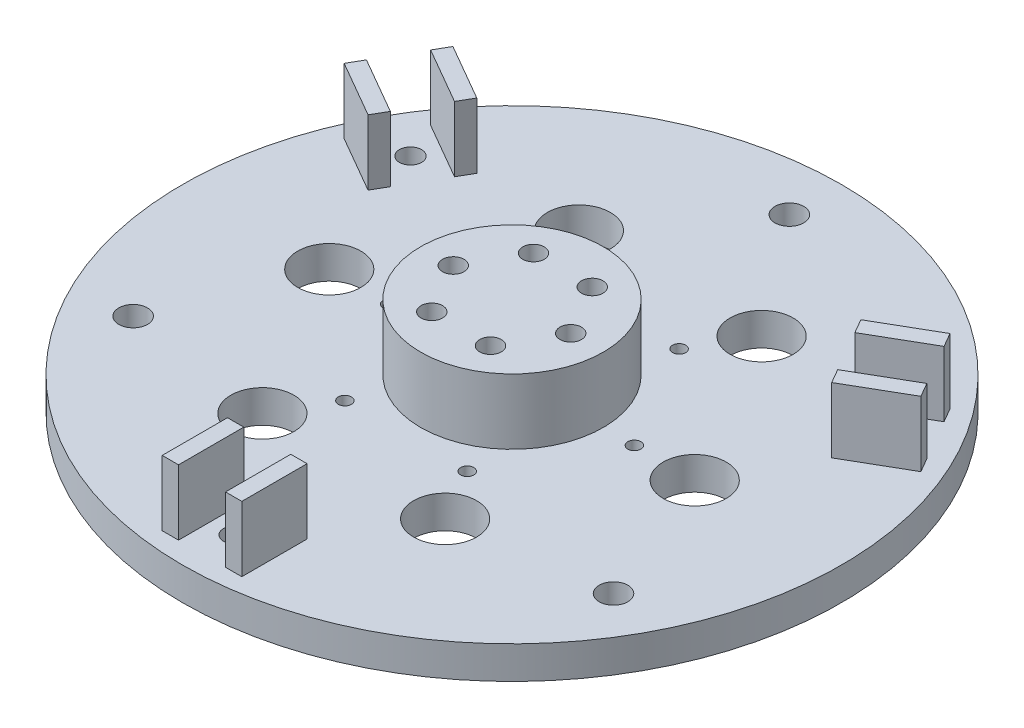
SolidWorks part; units mm, degrees
ref_plane "Front Plane" through (0, 0, 0) normal (0, 0, 1) x (1, 0, 0)
ref_plane "Top Plane" through (0, 0, 0) normal (0, 1, 0) x (1, 0, 0)
ref_plane "Right Plane" through (0, 0, 0) normal (1, 0, 0) x (0, 0, -1)
sketch "Sketch1" plane through (0, 0, 0) normal (0, 1, 0) x (1, 0, 0)
  circle A0 centre (0, 0) radius 50.5
  dimension "D1" = 101
extrude "Boss-Extrude1" add sketch "Sketch1" along normal blind 5
sketch "Sketch3" plane through (0, 5, 0) normal (0, 1, 0) x (1, 0, 0)
  circle A0 centre (9, 0) radius 1.65
  circle A2 centre (4.5, -7.7942) radius 1.65
  circle A3 centre (-4.5, -7.7942) radius 1.65
  circle A4 centre (-9, 0) radius 1.65
  circle A5 centre (-4.5, 7.7942) radius 1.65
  circle A6 centre (4.5, 7.7942) radius 1.65
  circle A7 centre (0, 0) radius 14
  point P13 (0, 0)
  dimension "D2" = 3.3
  dimension "D3" = 6
  dimension "D4" = 28
  dimension "D1" = 9
extrude "Boss-Extrude2" add sketch "Sketch3" along normal blind 10
sketch "Sketch6" plane through (0, 5, 0) normal (0, 1, 0) x (1, 0, 0)
  line L1 (0, 0) -> (69.3461, 0) construction
  circle A0 centre (0, 0) radius 18.75 construction
  circle A3 centre (18.75, 0) radius 1
  circle A5 centre (9.375, -16.238) radius 1
  circle A6 centre (-9.375, -16.238) radius 1
  circle A7 centre (-18.75, 0) radius 1
  circle A8 centre (-9.375, 16.238) radius 1
  circle A9 centre (9.375, 16.238) radius 1
  point P18 (0, 0)
  point P22 (0, 0)
  dimension "D1" = 37.5
  dimension "D2" = 2
  dimension "D3" = 6
extrude "Cut-Extrude4" cut sketch "Sketch6" against normal blind 10
sketch "Sketch5" plane through (0, 5, 0) normal (0, 1, 0) x (1, 0, 0)
  circle A0 centre (0, 0) radius 28 construction
  circle A1 centre (28, 0) radius 4.835
  circle A5 centre (14, -24.2487) radius 4.835
  circle A6 centre (-14, -24.2487) radius 4.835
  circle A7 centre (-28, 0) radius 4.835
  circle A8 centre (-14, 24.2487) radius 4.835
  circle A9 centre (14, 24.2487) radius 4.835
  point P17 (0, 0)
  dimension "D1" = 56
  dimension "D2" = 9.67
  dimension "D3" = 6
extrude "Cut-Extrude3" cut sketch "Sketch5" against normal through all
sketch "Sketch12" plane through (0, 0, 0) normal (0, -1, 0) x (1, 0, 0)
  line L2 (0, 0) -> (0, 50.5) construction
  circle A0 centre (14, 24.2487) radius 4.835 construction
  circle A1 centre (14, 24.2487) radius 4.835 construction
  circle A2 centre (0, 0) radius 50.5 construction
  circle A4 centre (0, 42.5) radius 1.7
  dimension "D2" = 3.4
  dimension "D1" = 42.5
extrude "Cut-Extrude10" cut sketch "Sketch12" against normal up to next
sketch "Sketch15" plane through (0, 5, 0) normal (0, -1, 0) x (1, 0, 0)
  line L1 (-3.6, 37.5) -> (3.6, 37.5) construction
  line L2 (-3.6, 37.5) -> (-3.6, 47.5) construction
  line L3 (-3.6, 47.5) -> (3.6, 47.5) construction
  line L4 (3.6, 37.5) -> (3.6, 47.5) construction
  line L5 (-3.6, 37.5) -> (3.6, 47.5) construction
  line L6 (-3.6, 47.5) -> (3.6, 37.5) construction
  line L7 (-3.6, 47.5) -> (-6.1, 47.5)
  line L8 (-3.6, 47.5) -> (-3.6, 37.5)
  line L9 (-3.6, 37.5) -> (-6.1, 37.5)
  line L10 (-6.1, 47.5) -> (-6.1, 37.5)
  line L11 (3.6, 47.5) -> (6.1, 47.5)
  line L12 (3.6, 47.5) -> (3.6, 37.5)
  line L13 (3.6, 37.5) -> (6.1, 37.5)
  line L14 (6.1, 47.5) -> (6.1, 37.5)
  point P0 (0, 42.5)
  dimension "D1" = 7.2
  dimension "D2" = 10
  dimension "D3" = 2.5
  dimension "D4" = 2.5
extrude "Boss-Extrude3" add sketch "Sketch15" against normal blind 10
sketch "Sketch13" plane through (0, 5, 0) normal (0, 1, 0) x (1, 0, 0)
  line L0 (0, 0) -> (0, 50.5) construction
  circle A0 centre (0, 0) radius 50.5 construction
  circle A1 centre (0, 42.5) radius 2.2
  dimension "D1" = 4.4
  dimension "D2" = 42.5
extrude "Cut-Extrude11" cut sketch "Sketch13" against normal up to next
pattern_circular "CirPattern1" count 3 over 360 about axis through (0, 0, 0) along (0, 1, 0) of "Cut-Extrude10", "Cut-Extrude11", "Boss-Extrude3"
